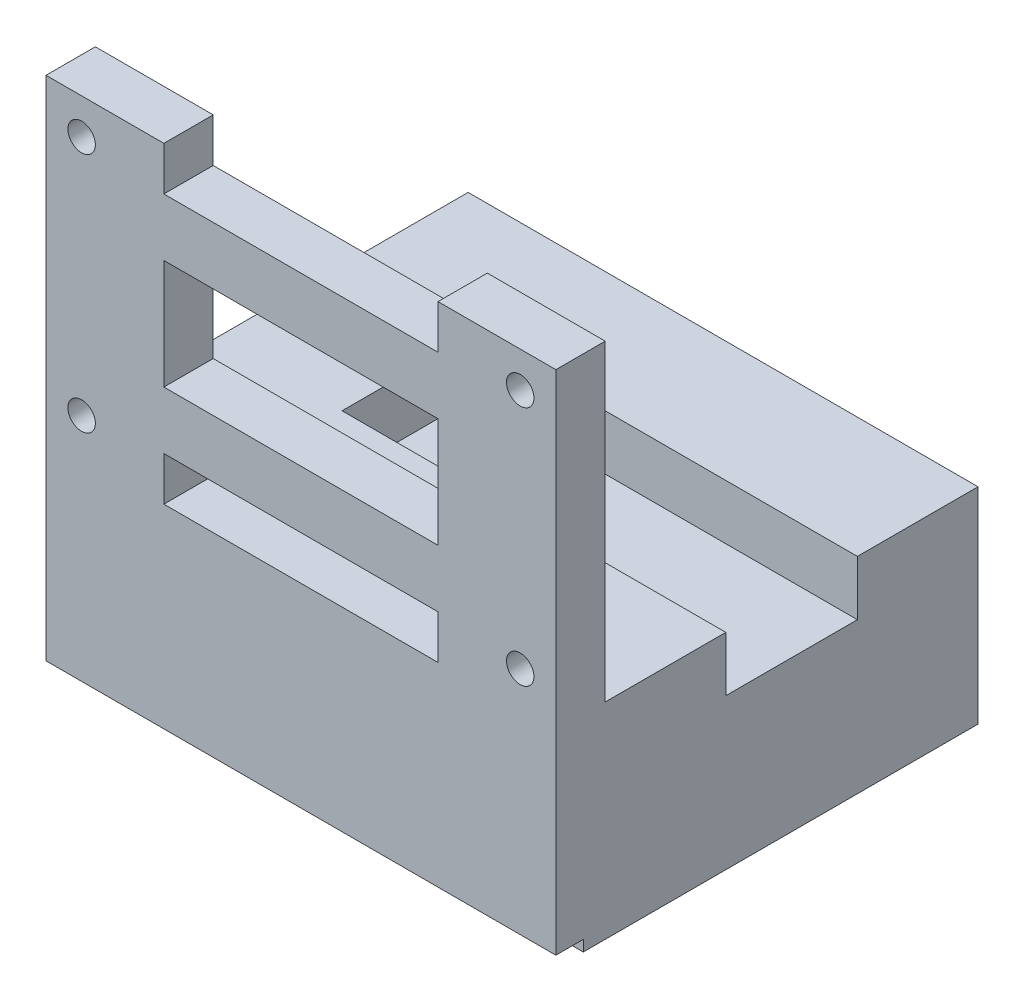
SolidWorks part; units mm, degrees
ref_plane "Front Plane" through (0, 0, 0) normal (0, 0, 1) x (1, 0, 0)
ref_plane "Top Plane" through (0, 0, 0) normal (0, 1, 0) x (1, 0, 0)
ref_plane "Right Plane" through (0, 0, 0) normal (1, 0, 0) x (0, 0, -1)
sketch "Sketch1" plane through (0, 0, 0) normal (0, 1, 0) x (1, 0, 0)
  line L1 (-23.25, -17) -> (23.25, -17)
  line L2 (-23.25, -17) -> (-23.25, 17)
  line L3 (-23.25, 17) -> (23.25, 17)
  line L4 (23.25, -17) -> (23.25, 17)
  line L5 (-23.25, -17) -> (23.25, 17) construction
  line L6 (-23.25, 17) -> (23.25, -17) construction
  point P0 (0, 0)
  dimension "D1" = 46.5
  dimension "D2" = 34
extrude "Boss-Extrude1" add sketch "Sketch1" along normal blind 13.75
sketch "Sketch2" plane through (0, 0, 17) normal (0, 0, 1) x (1, 0, 0)
  line L1 (-23.25, 0) -> (23.25, 0)
  line L2 (-23.25, 0) -> (-23.25, 42.25)
  line L3 (-23.25, 42.25) -> (23.25, 42.25)
  line L4 (23.25, 0) -> (23.25, 42.25)
  dimension "D1" = 46.5
  dimension "D2" = 42.25
extrude "Boss-Extrude2" add sketch "Sketch2" along normal blind 2
sketch "Sketch4" plane through (0, 13.75, 0) normal (0, 1, 0) x (1, 0, 0)
  line L0 (23.25, -17) -> (23.25, 17) construction
  line L1 (23.25, 6) -> (-11.75, 6)
  line L2 (23.25, 6) -> (23.25, -6)
  line L3 (23.25, -6) -> (-11.75, -6)
  line L4 (-11.75, 6) -> (-11.75, -6)
  line L5 (23.25, 17) -> (-23.25, 17) construction
  dimension "D1" = 35
  dimension "D2" = 12
  dimension "D3" = 11
extrude "Cut-Extrude2" cut sketch "Sketch4" against normal blind 5
sketch "Sketch6" plane through (0, 0, 0) normal (0, -1, 0) x (1, 0, 0)
  line L0 (16.25, -10) -> (16.25, 12)
  line L1 (23.25, -17) -> (-23.25, -17)
  line L2 (23.25, -17) -> (23.25, 19)
  line L3 (23.25, 19) -> (-23.25, 19)
  line L4 (-23.25, -17) -> (-23.25, 19)
  line L5 (16.25, 12) -> (-16.25, 12)
  line L6 (-16.25, -10) -> (-16.25, 12)
  line L7 (16.25, -10) -> (-16.25, -10)
  circle A0 centre (16.25, -10) radius 2
  circle A1 centre (16.25, 12) radius 2
  circle A2 centre (-16.25, -10) radius 2
  circle A3 centre (-16.25, 12) radius 2
  line M9 (23.25, -17) -> (23.25, 19)
  line M10 (23.25, 19) -> (-23.25, 19)
  line M11 (-23.25, 19) -> (-23.25, -17)
  line M12 (-23.25, -17) -> (23.25, -17)
  dimension "D2" = 4
  dimension "D3" = 4
  dimension "D4" = 4
  dimension "D5" = 4
  dimension "D1" = 7
extrude "Boss-Extrude3" add sketch "Sketch6" along normal blind 5 contours A3 L6 A2 L7 A0 L0 A1 L5 | A3 L5 A1 L0 A0 L7 A2 L6 M12 M9 M10 M11
ref_plane "Plane1" through (0, -4, 0) normal (0, -1, 0) x (-1, 0, 0)
sketch "Sketch8" plane through (0, -4, 0) normal (0, -1, 0) x (-1, 0, 0)
  line L1 (-23.25, -19) -> (23.25, -19)
  line L2 (-23.25, -19) -> (-23.25, -21.5)
  line L3 (-23.25, -21.5) -> (23.25, -21.5)
  line L4 (23.25, -19) -> (23.25, -21.5)
  dimension "D1" = 46.5
  dimension "D2" = 2.5
extrude "Boss-Extrude4" add sketch "Sketch8" against normal blind 46.25
sketch "Sketch3" plane through (0, 0, 19) normal (0, 0, 1) x (1, 0, 0)
  line L0 (-23.25, 28) -> (23.25, 28) construction
  line L1 (-12.5, 33) -> (12.5, 33)
  line L2 (-12.5, 33) -> (-12.5, 23)
  line L3 (-12.5, 23) -> (12.5, 23)
  line L4 (12.5, 33) -> (12.5, 23)
  line L5 (23.25, -5) -> (23.25, -4) construction
  line L6 (23.25, 42.25) -> (-23.25, 42.25) construction
  line L7 (-23.25, -4) -> (-23.25, -5) construction
  circle A0 centre (-20, 39) radius 1.25
  circle A2 centre (20, 39) radius 1.25
  circle A4 centre (20, 17) radius 1.25
  circle A5 centre (-20, 17) radius 1.25
  dimension "D1" = 2.5
  dimension "D11" = 2.5
  dimension "D2" = 10
  dimension "D3" = 25
  dimension "D4" = 5
  dimension "D5" = 10.75
  dimension "D6" = 14.25
  dimension "D7" = 3.25
  dimension "D8" = 3.25
  dimension "D9" = 3.25
  dimension "D10" = 3.25
extrude "Cut-Extrude1" cut sketch "Sketch3" against normal up to next and the other way blind 51
sketch "Sketch7" plane through (0, 0, 17) normal (0, 0, -1) x (-1, 0, 0)
  line L0 (23.25, 13.75) -> (-23.25, 13.75) construction
  line L1 (-12.5, 13.75) -> (12.5, 13.75)
  line L2 (-12.5, 13.75) -> (-12.5, 17.75)
  line L3 (-12.5, 17.75) -> (12.5, 17.75)
  line L4 (12.5, 13.75) -> (12.5, 17.75)
  line L5 (-23.25, 42.25) -> (23.25, 42.25) construction
  line L6 (-12.5, 42.25) -> (12.5, 42.25)
  line L7 (-12.5, 42.25) -> (-12.5, 38.25)
  line L8 (-12.5, 38.25) -> (12.5, 38.25)
  line L9 (12.5, 42.25) -> (12.5, 38.25)
  dimension "D1" = 4
  dimension "D2" = 4
extrude "Cut-Extrude3" cut sketch "Sketch7" against normal blind 10
